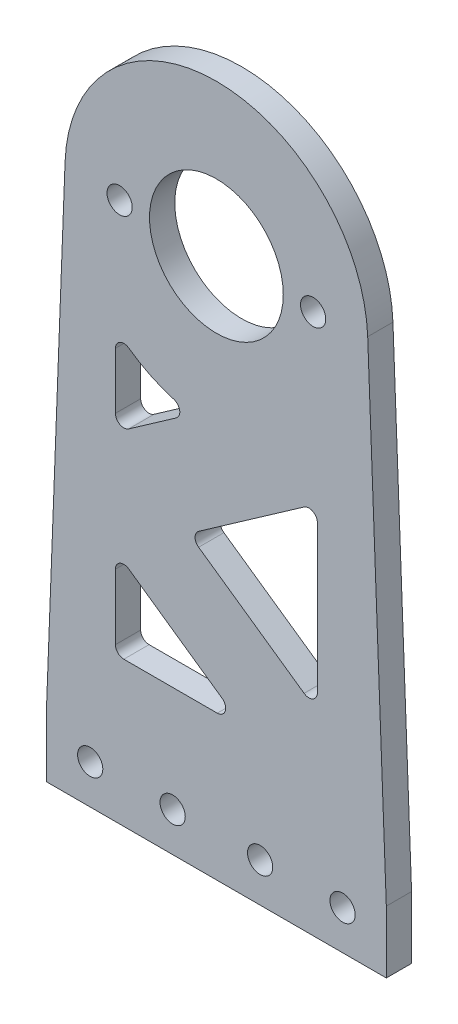
SolidWorks part; units mm, degrees
material "Acrylic (Medium-high impact)"
ref_plane "Front Plane" through (0, 0, 0) normal (0, 0, 1) x (1, 0, 0)
ref_plane "Top Plane" through (0, 0, 0) normal (0, 1, 0) x (1, 0, 0)
ref_plane "Right Plane" through (0, 0, 0) normal (1, 0, 0) x (0, 0, -1)
sketch "Sketch1" plane through (0, 0, 0) normal (0, 0, 1) x (1, 0, 0)
  line L0 (-11.1, 83.4741) -> (-9.1, 83.4741)
  line L1 (0, 41.6741) -> (20.2, 41.6741) construction
  line L2 (20.2, 41.6741) -> (20.2, 83.4741) construction
  line L3 (0, 83.4741) -> (9.1, 83.4741)
  line L4 (10.1, 83.4741) -> (10.1, 41.6741) construction
  line L5 (0, 62.5741) -> (20.2, 62.5741) construction
  line L6 (-20.2, 83.4741) -> (-20.2, 41.6741) construction
  line L7 (-20.2, 41.6741) -> (0, 41.6741) construction
  line L8 (-20.2, 83.4741) -> (-11.1, 83.4741)
  line L9 (-10.1, 83.4741) -> (-10.1, 41.6741) construction
  line L10 (-20.2, 62.5741) -> (0, 62.5741) construction
  line L11 (-20.2, 41.6741) -> (-17.9755, -0.9384) construction
  line L12 (20.2, 41.6741) -> (17.9755, -0.9384) construction
  line L13 (0, 0) -> (0, 147.6909) construction
  line L14 (-20.2, 90.8741) -> (-17.9867, 148.3831)
  line L15 (20.2, 90.8741) -> (17.9867, 148.3831)
  line L16 (11.1, 83.4741) -> (20.2, 83.4741)
  line L17 (-11.1, 83.4741) -> (-11.1, 89.4741) construction
  line L18 (-11.1, 89.4741) -> (-9.1, 89.4741) construction
  line L19 (-9.1, 83.4741) -> (-9.1, 89.4741) construction
  line L20 (11.1, 83.4741) -> (9.1, 83.4741)
  line L21 (11.1, 83.4741) -> (11.1, 89.4741) construction
  line L22 (11.1, 89.4741) -> (9.1, 89.4741) construction
  line L23 (9.1, 83.4741) -> (9.1, 89.4741) construction
  line L24 (-9.1, 83.4741) -> (0, 83.4741)
  line L25 (-20.2, 90.8741) -> (20.2, 90.8741) construction
  line L26 (-20.2, 83.4741) -> (-20.2, 90.8741)
  line L27 (20.2, 83.4741) -> (20.2, 90.8741)
  circle A0 centre (10.1, 73.3741) radius 6.5 construction
  arc A1 (-17.9755, -0.9384) -> (17.9755, -0.9384) centre (0, 0) cw construction
  circle A2 centre (0, 0) radius 2.5 construction
  arc A3 (-17.9755, -0.9384) -> (17.9755, -0.9384) centre (0, 0) ccw construction
  circle A4 centre (5.2, 88.1241) radius 1.5
  circle A5 centre (15, 88.1241) radius 1.5
  circle A6 centre (-10.1, 51.7741) radius 6.5 construction
  circle A7 centre (-15, 88.1241) radius 1.5
  circle A8 centre (-5.2, 88.1241) radius 1.5
  circle A9 centre (-15, 37.0241) radius 1.5 construction
  circle A10 centre (-5.2, 37.0241) radius 1.5 construction
  circle A11 centre (0, 0) radius 52.75 construction
  circle A12 centre (5.2, 37.0241) radius 1.5 construction
  circle A13 centre (15, 37.0241) radius 1.5 construction
  arc A14 (17.9867, 148.3831) -> (-17.9867, 148.3831) centre (0, 147.6909) ccw
  circle A15 centre (0, 147.6909) radius 7.95
  circle A16 centre (10.1, 73.3741) radius 75 construction
  dimension "D1" = 5
  dimension "D2" = 18
  dimension "D10" = 51.1
  dimension "D3" = 13
  dimension "D4" = 3
  dimension "D8" = 9.8
  dimension "D9" = 105.5
  dimension "D5" = 20.2
  dimension "D19" = 36
  dimension "D20" = 15.9
  dimension "D18" = 150
  dimension "D6" = 10.1
  dimension "D7" = 41.8
  dimension "D13" = 10.1
  dimension "D14" = 6
  dimension "D15" = 9.8
  dimension "D16" = 2
  dimension "D21" = 7.4
extrude "Main Body Link B1" add sketch "Sketch1" along normal blind 3
sketch "Sketch2" plane through (0, 0, 3) normal (0, 0, 1) x (1, 0, 0)
  line L0 (0, 147.6909) -> (0, 83.4741) construction
  line L1 (-12, 134.2745) -> (12, 134.2745) construction
  line L2 (-12, 134.2745) -> (-12, 123.585)
  line L3 (-12, 100.6909) -> (3.2782, 100.6909)
  line L4 (12, 128.1722) -> (12, 106.7932)
  line L5 (-12, 117.4827) -> (12, 117.4827) construction
  line L6 (-12, 111.3804) -> (-12, 100.6909)
  line L7 (12, 100.6909) -> (-12, 117.4827) construction
  line L8 (-12, 117.4827) -> (12, 134.2745) construction
  line L9 (3.2782, 100.6909) -> (-12, 111.3804)
  line L10 (-12, 123.585) -> (-2.9299, 129.9309)
  line L12 (-3.2782, 117.4827) -> (12, 106.7932)
  line L13 (-3.2782, 117.4827) -> (12, 128.1722)
  line L14 (3.2782, 100.6909) -> (12, 100.6909) construction
  line L15 (12, 100.6909) -> (12, 106.7932) construction
  line L16 (-12, 123.585) -> (-12, 117.4827) construction
  line L17 (-12, 117.4827) -> (-12, 111.3804) construction
  line L19 (12, 134.2745) -> (12, 128.1722) construction
  line L20 (-20.2, 83.4741) -> (20.2, 83.4741) construction
  arc A0 (-12, 134.2745) -> (-2.9299, 129.9309) centre (0, 147.6909) ccw
  arc A1 (-17.9867, 148.3831) -> (-12, 134.2745) centre (0, 147.6909) ccw construction
  arc A2 (12, 134.2745) -> (17.9867, 148.3831) centre (0, 147.6909) ccw construction
  arc A3 (17.9867, 148.3831) -> (-17.9867, 148.3831) centre (0, 147.6909) ccw construction
  dimension "D1" = 24
  dimension "D2" = 47
  dimension "D4" = 10
extrude "Cut-Extrude1" cut sketch "Sketch2" against normal up to next contours L13 L12 L4 | A0 L2 L10 | L6 L3 L9
sketch "Sketch3" plane through (0, 0, 3) normal (0, 0, 1) x (1, 0, 0)
  line L0 (0, 147.6909) -> (0, 139.7409) construction
  circle A0 centre (-11.5, 147.6909) radius 1.5
  circle A1 centre (11.5, 147.6909) radius 1.5
  circle A2 centre (0, 147.6909) radius 7.95 construction
  dimension "D1" = 3
  dimension "D2" = 11.5
extrude "Cut-Extrude2" cut sketch "Sketch3" against normal up to next
fillet "Fillet1" radius 1 9 edges at (-12, 100.6909, 1.5) (3.2782, 100.6909, 1.5) (-12, 111.3804, 1.5) (12, 106.7932, 1.5) (12, 128.1722, 1.5) (-3.2782, 117.4827, 1.5) (-12, 123.585, 1.5) (-2.9299, 129.9309, 1.5) (-12, 134.2745, 1.5)
equation "\"D20@Sketch1\"=16.00mm-+\"radii_fit@Parameters@Parameters.SLDPRT\""
equation "\"D9@Sketch1\"=\"CenterDist2@Parameters@Parameters.SLDPRT\"*2"
equation "\"D18@Sketch1\"=\"CenterDist3@Parameters@Parameters.SLDPRT\"*2"
